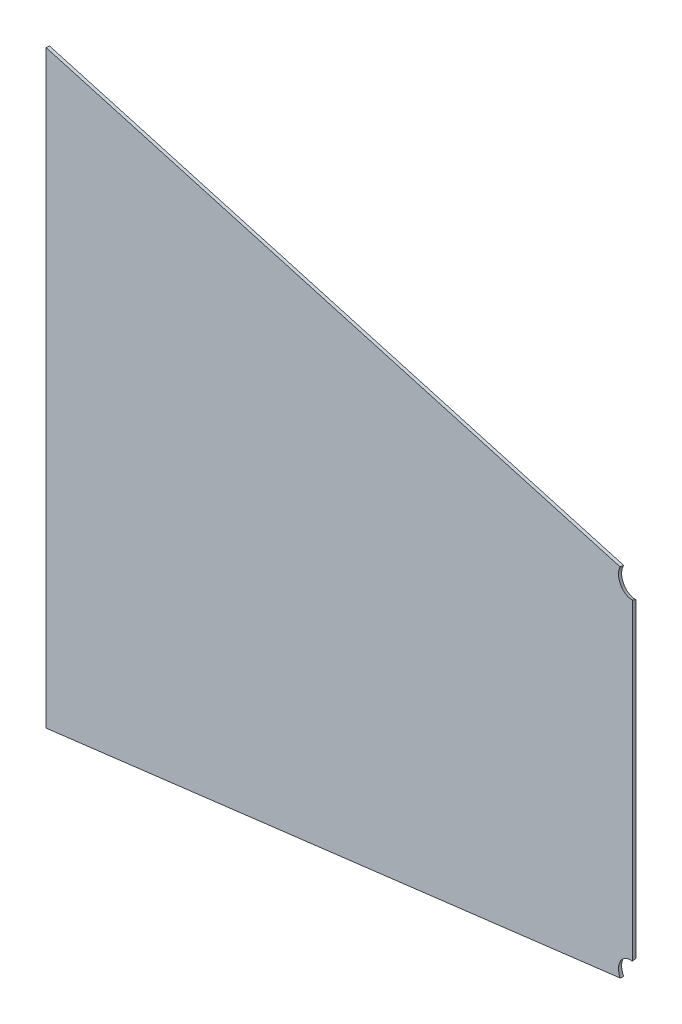
SolidWorks part; units mm, degrees
material "6061-T6 (SS)"
ref_plane "X-Y Datum" through (0, 0, 0) normal (0, 0, 1) x (1, 0, 0)
ref_plane "X-Z Datum" through (0, 0, 0) normal (0, 1, 0) x (1, 0, 0)
ref_plane "Y-Z Datum" through (0, 0, 0) normal (1, 0, 0) x (0, 0, -1)
ref_plane "Plane1" through (1.0099, 0, -13.5995) normal (0.0741, 0, -0.9973) x (-0.9973, 0, -0.0741)
ref_plane "Plane2" through (1.9503, 0, -26.2646) normal (0.0741, 0, -0.9973) x (-0.9973, 0, -0.0741)
sketch "Sketch1" plane through (1.9503, 0, -26.2646) normal (0.0741, 0, -0.9973) x (-0.9973, 0, -0.0741)
  line L0 (-183.6444, -298.45) -> (-183.6444, 298.45) construction
  line L1 (-183.6444, -298.45) -> (-826.7602, -177.8) construction
  line L2 (-826.7602, -177.8) -> (-826.7602, 177.8) construction
  line L3 (-826.7602, 177.8) -> (-183.6444, 298.45) construction
  line L4 (-183.6444, -298.45) -> (-183.6444, 298.45)
  line L5 (-183.6444, -298.45) -> (-826.7602, -177.8)
  line L6 (-826.7602, -177.8) -> (-826.7602, 177.8)
  line L7 (-826.7602, 177.8) -> (-183.6444, 298.45)
extrude "Boss-Extrude1" add sketch "Sketch1" along normal blind 3.175
ref_plane "Plane3" through (825.5, 212.9428, 150.983) normal (0, 0.3219, 0.9468) x (1, 0, 0)
sketch "Sketch2" plane through (825.5, 212.9428, 150.983) normal (0, 0.3219, 0.9468) x (1, 0, 0)
  circle A0 centre (0, 0) radius 14.2875
  dimension "D1" = 28.575
extrude "Cut-Extrude1" cut sketch "Sketch2" against normal through all contours A0
mirror "Mirror1" about plane through (0, 0, 0) normal (0, 1, 0) of "Cut-Extrude1"
